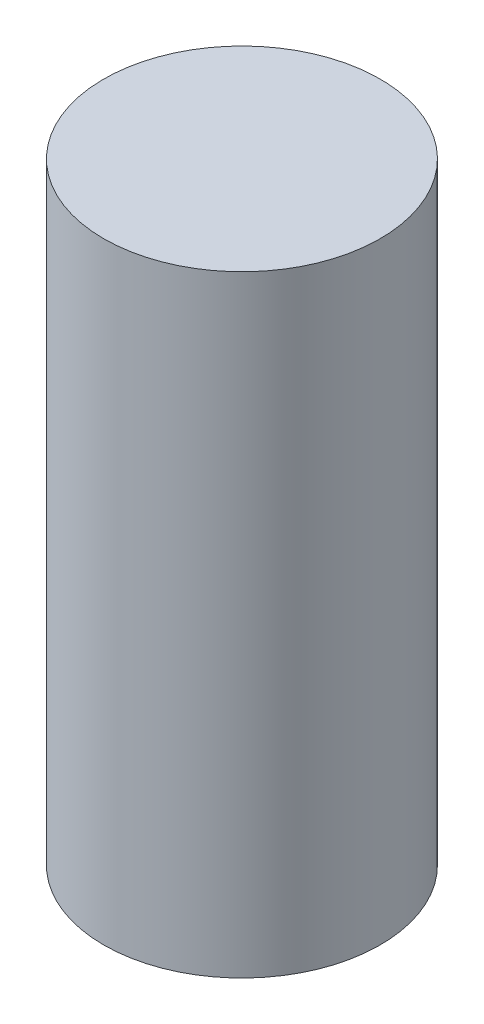
SolidWorks part; units mm, degrees
ref_plane "Front Plane" through (0, 0, 0) normal (0, 0, 1) x (1, 0, 0)
ref_plane "Top Plane" through (0, 0, 0) normal (0, 1, 0) x (1, 0, 0)
ref_plane "Right Plane" through (0, 0, 0) normal (1, 0, 0) x (0, 0, -1)
sketch "Sketch1" plane through (0, 0, 0) normal (0, 1, 0) x (1, 0, 0)
  circle A0 centre (0, 0) radius 33
  dimension "D1" = 66
extrude "Boss-Extrude1" add sketch "Sketch1" along normal blind 146
